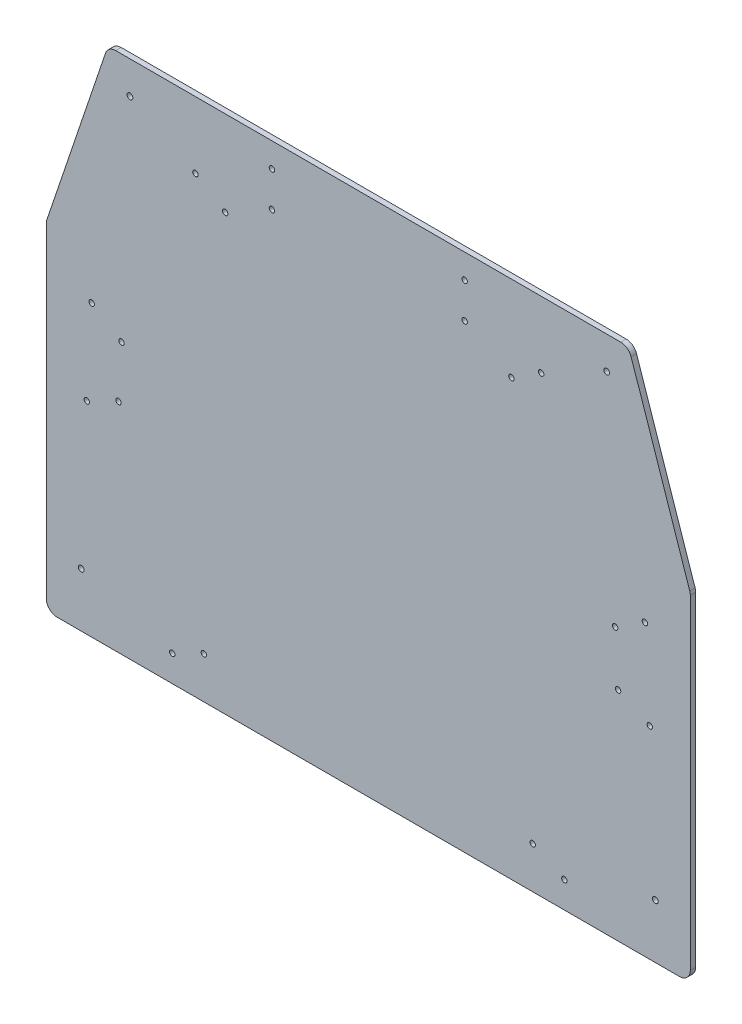
SolidWorks part; units mm, degrees
material "PC High Viscosity"
ref_plane "Front Plane" through (0, 0, 0) normal (0, 0, 1) x (1, 0, 0)
ref_plane "Top Plane" through (0, 0, 0) normal (0, 1, 0) x (1, 0, 0)
ref_plane "Right Plane" through (0, 0, 0) normal (1, 0, 0) x (0, 0, -1)
sketch "Sketch1" plane through (0, 0, 0) normal (0, 0, 1) x (1, 0, 0)
  line L0 (128.5466, 292.9716) -> (382.5466, 292.9716)
  line L5 (382.5466, 292.9716) -> (776.2466, -872.6346)
  line L6 (776.2466, -872.6346) -> (-265.1534, -872.6346)
  line L7 (-265.1534, -872.6346) -> (128.5466, 292.9716)
  line L8 (-168.2075, -740.392) -> (-160.0795, -716.3277) construction
  line L9 (-180.2397, -736.328) -> (-172.1116, -712.2636)
  line L10 (-156.1753, -744.4561) -> (-148.0473, -720.3917)
  line L11 (-94.2317, -804.0546) -> (-68.8317, -804.0546) construction
  line L12 (-94.2317, -791.3546) -> (-68.8317, -791.3546)
  line L13 (-94.2317, -816.7546) -> (-68.8317, -816.7546)
  line L14 (580.5201, -804.0546) -> (605.9201, -804.0546) construction
  line L15 (580.5201, -791.3546) -> (605.9201, -791.3546)
  line L16 (580.5201, -816.7546) -> (605.9201, -816.7546)
  line L17 (-56.7399, -410.3759) -> (-48.6118, -386.3115) construction
  line L18 (-68.7721, -406.3118) -> (-60.644, -382.2474)
  line L19 (-44.7077, -414.4399) -> (-36.5796, -390.3755)
  line L20 (45.2346, -108.4656) -> (53.3626, -84.4012) construction
  line L21 (33.2024, -104.4015) -> (41.3305, -80.3372)
  line L22 (57.2668, -112.5296) -> (65.3948, -88.4652)
  line L29 (139.9814, 172.0464) -> (148.1095, 196.1108) construction
  line L30 (127.9493, 176.1104) -> (136.0773, 200.1748)
  line L31 (152.0136, 167.9823) -> (160.1417, 192.0467)
  line L32 (192.1135, 241.2472) -> (217.5135, 241.2472) construction
  line L33 (192.1135, 253.9472) -> (217.5135, 253.9472)
  line L34 (192.1135, 228.5472) -> (217.5135, 228.5472)
  line L35 (293.6466, 241.2472) -> (319.0466, 241.2472) construction
  line L36 (293.6466, 253.9472) -> (319.0466, 253.9472)
  line L37 (293.6466, 228.5472) -> (319.0466, 228.5472)
  line L38 (371.0972, 172.0897) -> (362.9691, 196.154) construction
  line L39 (359.065, 168.0256) -> (350.9369, 192.09)
  line L40 (383.1294, 176.1537) -> (375.0013, 200.2181)
  line L41 (465.8587, -108.4656) -> (457.7306, -84.4012) construction
  line L42 (453.8265, -112.5296) -> (445.6984, -88.4652)
  line L43 (477.8909, -104.4015) -> (469.7628, -80.3372)
  line L44 (679.3008, -740.392) -> (671.1727, -716.3277) construction
  line L47 (567.8332, -410.3759) -> (559.7051, -386.3115) construction
  line L48 (555.801, -414.4399) -> (547.6729, -390.3755)
  line L49 (579.8654, -406.3118) -> (571.7373, -382.2474)
  line L50 (667.2686, -744.4561) -> (659.1405, -720.3917)
  line L53 (691.333, -736.328) -> (683.2049, -712.2636)
  circle A0 centre (396.7562, 191.3716) radius 5.3578
  circle A1 centre (114.6592, 192.3252) radius 5.3578
  circle A2 centre (-193.5708, -720.2346) radius 5.3578
  circle A4 centre (704.6641, -720.2346) radius 5.3578
  circle A5 centre (491.1275, -88.0284) radius 5.3578
  circle A6 centre (593.2201, -390.2884) radius 5.3578
  circle A7 centre (19.9658, -88.0284) radius 5.3578
  circle A8 centre (-82.1268, -390.2884) radius 5.3578
  circle A9 centre (306.3466, 271.7272) radius 5.3578
  circle A10 centre (204.7466, 271.7272) radius 5.3578
  circle A12 centre (-82.1268, -834.5346) radius 5.3578
  circle A13 centre (593.2201, -834.5346) radius 5.3578
  arc A14 (-180.2397, -736.328) -> (-156.1753, -744.4561) centre (-168.2075, -740.392) ccw
  arc A15 (-148.0473, -720.3917) -> (-172.1116, -712.2636) centre (-160.0795, -716.3277) ccw
  arc A16 (-94.2317, -791.3546) -> (-94.2317, -816.7546) centre (-94.2317, -804.0546) ccw
  arc A17 (-68.8317, -816.7546) -> (-68.8317, -791.3546) centre (-68.8317, -804.0546) ccw
  arc A18 (580.5201, -791.3546) -> (580.5201, -816.7546) centre (580.5201, -804.0546) ccw
  arc A19 (605.9201, -816.7546) -> (605.9201, -791.3546) centre (605.9201, -804.0546) ccw
  arc A20 (-68.7721, -406.3118) -> (-44.7077, -414.4399) centre (-56.7399, -410.3759) ccw
  arc A21 (-36.5796, -390.3755) -> (-60.644, -382.2474) centre (-48.6118, -386.3115) ccw
  arc A22 (33.2024, -104.4015) -> (57.2668, -112.5296) centre (45.2346, -108.4656) ccw
  arc A23 (65.3948, -88.4652) -> (41.3305, -80.3372) centre (53.3626, -84.4012) ccw
  arc A28 (127.9493, 176.1104) -> (152.0136, 167.9823) centre (139.9814, 172.0464) ccw
  arc A29 (160.1417, 192.0467) -> (136.0773, 200.1748) centre (148.1095, 196.1108) ccw
  arc A30 (192.1135, 253.9472) -> (192.1135, 228.5472) centre (192.1135, 241.2472) ccw
  arc A31 (217.5135, 228.5472) -> (217.5135, 253.9472) centre (217.5135, 241.2472) ccw
  arc A32 (293.6466, 253.9472) -> (293.6466, 228.5472) centre (293.6466, 241.2472) ccw
  arc A33 (319.0466, 228.5472) -> (319.0466, 253.9472) centre (319.0466, 241.2472) ccw
  arc A34 (359.065, 168.0256) -> (383.1294, 176.1537) centre (371.0972, 172.0897) ccw
  arc A35 (375.0013, 200.2181) -> (350.9369, 192.09) centre (362.9691, 196.154) ccw
  arc A36 (453.8265, -112.5296) -> (477.8909, -104.4015) centre (465.8587, -108.4656) ccw
  arc A37 (469.7628, -80.3372) -> (445.6984, -88.4652) centre (457.7306, -84.4012) ccw
  arc A40 (555.801, -414.4399) -> (579.8654, -406.3118) centre (567.8332, -410.3759) ccw
  arc A41 (571.7373, -382.2474) -> (547.6729, -390.3755) centre (559.7051, -386.3115) ccw
  arc A44 (667.2686, -744.4561) -> (691.333, -736.328) centre (679.3008, -740.392) ccw
  arc A45 (683.2049, -712.2636) -> (659.1405, -720.3917) centre (671.1727, -716.3277) ccw
  point P24 (-164.1435, -728.3598)
  point P39 (-81.5317, -804.0546)
  point P47 (593.2201, -804.0546)
  point P56 (-52.6759, -398.3437)
  point P62 (204.8135, 241.2472)
  point P65 (49.2986, -96.4334)
  point P93 (144.0455, 184.0786)
  point P106 (306.3466, 241.2472)
  point P115 (367.0332, 184.1219)
  point P125 (461.7947, -96.4334)
  point P136 (675.2368, -728.3598)
  point P140 (563.7691, -398.3437)
  dimension "D5" = 10.7156
  dimension "D6" = 19.05
  dimension "D7" = 17.78
  dimension "D8" = 17.78
  dimension "D9" = 17.78
  dimension "D10" = 17.78
  dimension "D11" = 17.78
  dimension "D12" = 17.78
  dimension "D13" = 38.1
  dimension "D31" = 183.6216
  dimension "D32" = 144.2748
  dimension "D36" = 108.893
  dimension "D37" = 17.78
  dimension "D41" = 76.2669
  dimension "D34" = 776.2012
  dimension "D35" = 25.4
  dimension "D1" = 254
  dimension "D2" = 1230.2998
  dimension "D3" = 1230.2998
  dimension "D4" = 1041.4
  dimension "D14" = 19.05
  dimension "D15" = 683.26
  dimension "D16" = 19.05
  dimension "D17" = 76.2
  dimension "D18" = 381
  dimension "D19" = 683.26
  dimension "D20" = 152.4
  dimension "D21" = 152.4
  dimension "D22" = 19.05
  dimension "D23" = 76.2
  dimension "D24" = 19.05
  dimension "D25" = 381
  dimension "D26" = 101.6
  dimension "D27" = 19.05
  dimension "D28" = 19.05
  dimension "D29" = 19.05
  dimension "D30" = 101.6
  dimension "D33" = 474.291
  dimension "D38" = 38.1
  dimension "D39" = 25.4
  dimension "D40" = 17.78
  dimension "D42" = 17.78
  dimension "D43" = 108.8497
  dimension "D47" = 17.78
  dimension "D52" = 17.78
  dimension "D53" = 17.78
  dimension "D56" = 21.2444
  dimension "D57" = 21.2444
extrude "Boss-Extrude1" add sketch "Sketch1" along normal blind 6.35 contours L7 L6 L5 L0 A29 L31 A28 L30 A23 L22 A22 L21 A21 L19 A20 L18 A19 L16 A18 L15 A17 L13 A16 L12 A15 L10 A14 L9 A13 A12 A10 A9 A8 A7 A6 A5
fillet "Fillet1" radius 6.35 4 edges at (-265.1534, -872.6346, 3.175) (776.2466, -872.6346, 3.175) (382.5466, 292.9716, 3.175) (128.5466, 292.9716, 3.175)
sketch "Sketch2" plane through (0, 0, 6.35) normal (0, 0, 1) x (1, 0, 0)
  line L0 (255.5466, -872.6346) -> (255.5466, 292.9716) construction
  line L1 (767.3994, -872.6346) -> (-256.3061, -872.6346) construction
  line L2 (133.1043, 292.9716) -> (377.989, 292.9716) construction
  line L3 (91.6472, -808.2573) -> (67.9728, -842.0678)
  line L4 (443.1205, -842.0678) -> (419.4461, -808.2573)
  arc A0 (91.6472, -808.2573) -> (419.4461, -808.2573) centre (255.5466, -574.1846) cw
  arc A1 (67.9728, -842.0678) -> (443.1205, -842.0678) centre (255.5466, -574.1846) cw
  point P0 (255.5466, -288.4346)
  dimension "D3" = 298.45
  dimension "D1" = 41.275
  dimension "D2" = 584.2
  dimension "D4" = 70
sketch "Sketch4" plane through (0, 0, 6.35) normal (0, 0, 1) x (1, 0, 0)
  line L0 (414.1087, -288.4346) -> (255.5466, -288.4346)
  line L13 (414.1087, -288.4346) -> (572.6707, -563.0721)
  line L14 (572.6707, -563.0721) -> (414.1087, -837.7096)
  line L15 (767.3994, -872.6346) -> (-256.3061, -872.6346) construction
  line L16 (255.5466, -288.4346) -> (255.5466, -872.6346) construction
  line L17 (437.9388, -247.1596) -> (255.5466, -247.1596)
  line L18 (437.9388, -247.1596) -> (620.331, -563.0721)
  line L19 (620.331, -563.0721) -> (449.8539, -858.3471)
  line L20 (449.8539, -858.3471) -> (414.1087, -837.7096)
  line L21 (61.2394, -858.3471) -> (96.9846, -837.7096)
  line L22 (-109.2377, -563.0721) -> (61.2394, -858.3471)
  line L23 (73.1545, -247.1596) -> (-109.2377, -563.0721)
  line L24 (73.1545, -247.1596) -> (255.5466, -247.1596)
  line L25 (-61.5774, -563.0721) -> (96.9846, -837.7096)
  line L26 (96.9846, -288.4346) -> (-61.5774, -563.0721)
  line L27 (96.9846, -288.4346) -> (255.5466, -288.4346)
  line L28 (414.1087, -837.7096) -> (96.9846, -837.7096) construction
  dimension "D1" = 309.5625
  dimension "D2" = 317.1241
  dimension "D3" = 120
  dimension "D4" = 120
  dimension "D5" = 41.275
extrude "Cut-Extrude1" cut sketch "Sketch2" against normal through all
extrude "Cut-Extrude2" [suppressed] cut sketch "Sketch4" against normal through all
sketch "Sketch5" plane through (0, 0, 6.35) normal (0, 0, 1) x (1, 0, 0)
  line L0 (57.2668, -112.5296) -> (65.3948, -88.4652) construction
  line L1 (33.2024, -104.4015) -> (41.3305, -80.3372) construction
  line L2 (-44.7077, -414.4399) -> (-36.5796, -390.3755) construction
  line L3 (-68.7721, -406.3118) -> (-60.644, -382.2474) construction
  line L4 (-180.2397, -736.328) -> (-172.1116, -712.2636) construction
  line L5 (-156.1753, -744.4561) -> (-148.0473, -720.3917) construction
  line L6 (-94.2317, -816.7546) -> (-68.8317, -816.7546) construction
  line L7 (-94.2317, -791.3546) -> (-68.8317, -791.3546) construction
  line L8 (57.2668, -112.5296) -> (65.3948, -88.4652)
  line L9 (33.2024, -104.4015) -> (41.3305, -80.3372)
  line L10 (-44.7077, -414.4399) -> (-36.5796, -390.3755)
  line L11 (-68.7721, -406.3118) -> (-60.644, -382.2474)
  line L12 (-180.2397, -736.328) -> (-172.1116, -712.2636)
  line L13 (-156.1753, -744.4561) -> (-148.0473, -720.3917)
  line L14 (-94.2317, -816.7546) -> (-68.8317, -816.7546)
  line L15 (-94.2317, -791.3546) -> (-68.8317, -791.3546)
  line L16 (192.1135, 228.5472) -> (217.5135, 228.5472) construction
  line L17 (192.1135, 253.9472) -> (217.5135, 253.9472) construction
  line L18 (152.0136, 167.9823) -> (160.1417, 192.0467) construction
  line L19 (127.9493, 176.1104) -> (136.0773, 200.1748) construction
  line L20 (192.1135, 228.5472) -> (217.5135, 228.5472)
  line L21 (192.1135, 253.9472) -> (217.5135, 253.9472)
  line L22 (152.0136, 167.9823) -> (160.1417, 192.0467)
  line L23 (127.9493, 176.1104) -> (136.0773, 200.1748)
  line L24 (255.5466, 292.9716) -> (255.5466, -872.6346) construction
  line L37 (359.065, 168.0256) -> (350.9369, 192.09) construction
  line L38 (383.1294, 176.1537) -> (375.0013, 200.2181) construction
  line L39 (293.6466, 228.5472) -> (319.0466, 228.5472) construction
  line L40 (293.6466, 253.9472) -> (319.0466, 253.9472) construction
  line L41 (359.065, 168.0256) -> (350.9369, 192.09)
  line L42 (383.1294, 176.1537) -> (375.0013, 200.2181)
  line L43 (293.6466, 228.5472) -> (319.0466, 228.5472)
  line L44 (293.6466, 253.9472) -> (319.0466, 253.9472)
  line L45 (453.8265, -112.5296) -> (445.6984, -88.4652) construction
  line L46 (477.8909, -104.4015) -> (469.7628, -80.3372) construction
  line L47 (453.8265, -112.5296) -> (445.6984, -88.4652)
  line L48 (477.8909, -104.4015) -> (469.7628, -80.3372)
  line L49 (555.801, -414.4399) -> (547.6729, -390.3755) construction
  line L50 (579.8654, -406.3118) -> (571.7373, -382.2474) construction
  line L51 (555.801, -414.4399) -> (547.6729, -390.3755)
  line L52 (579.8654, -406.3118) -> (571.7373, -382.2474)
  line L53 (667.2686, -744.4561) -> (659.1405, -720.3917) construction
  line L54 (691.333, -736.328) -> (683.2049, -712.2636) construction
  line L55 (667.2686, -744.4561) -> (659.1405, -720.3917)
  line L56 (691.333, -736.328) -> (683.2049, -712.2636)
  line L57 (580.5201, -791.3546) -> (605.9201, -791.3546) construction
  line L58 (580.5201, -816.7546) -> (605.9201, -816.7546) construction
  line L59 (580.5201, -791.3546) -> (605.9201, -791.3546)
  line L60 (580.5201, -816.7546) -> (605.9201, -816.7546)
  arc A0 (33.2024, -104.4015) -> (57.2668, -112.5296) centre (45.2346, -108.4656) ccw construction
  arc A1 (65.3948, -88.4652) -> (41.3305, -80.3372) centre (53.3626, -84.4012) ccw construction
  circle A2 centre (19.9658, -88.0284) radius 5.3578 construction
  arc A3 (-68.7721, -406.3118) -> (-44.7077, -414.4399) centre (-56.7399, -410.3759) ccw construction
  circle A4 centre (-82.1268, -390.2884) radius 5.3578 construction
  arc A5 (-36.5796, -390.3755) -> (-60.644, -382.2474) centre (-48.6118, -386.3115) ccw construction
  circle A6 centre (-193.5708, -720.2346) radius 5.3578 construction
  arc A7 (-148.0473, -720.3917) -> (-172.1116, -712.2636) centre (-160.0795, -716.3277) ccw construction
  arc A8 (-180.2397, -736.328) -> (-156.1753, -744.4561) centre (-168.2075, -740.392) ccw construction
  arc A9 (-94.2317, -791.3546) -> (-94.2317, -816.7546) centre (-94.2317, -804.0546) ccw construction
  arc A10 (-68.8317, -816.7546) -> (-68.8317, -791.3546) centre (-68.8317, -804.0546) ccw construction
  circle A11 centre (-82.1268, -834.5346) radius 5.3578 construction
  arc A12 (33.2024, -104.4015) -> (57.2668, -112.5296) centre (45.2346, -108.4656) ccw
  arc A13 (65.3948, -88.4652) -> (41.3305, -80.3372) centre (53.3626, -84.4012) ccw
  circle A14 centre (19.9658, -88.0284) radius 5.3578
  arc A15 (-68.7721, -406.3118) -> (-44.7077, -414.4399) centre (-56.7399, -410.3759) ccw
  circle A16 centre (-82.1268, -390.2884) radius 5.3578
  arc A17 (-36.5796, -390.3755) -> (-60.644, -382.2474) centre (-48.6118, -386.3115) ccw
  circle A18 centre (-193.5708, -720.2346) radius 5.3578
  arc A19 (-148.0473, -720.3917) -> (-172.1116, -712.2636) centre (-160.0795, -716.3277) ccw
  arc A20 (-180.2397, -736.328) -> (-156.1753, -744.4561) centre (-168.2075, -740.392) ccw
  arc A21 (-94.2317, -791.3546) -> (-94.2317, -816.7546) centre (-94.2317, -804.0546) ccw
  arc A22 (-68.8317, -816.7546) -> (-68.8317, -791.3546) centre (-68.8317, -804.0546) ccw
  circle A23 centre (-82.1268, -834.5346) radius 5.3578
  arc A24 (217.5135, 228.5472) -> (217.5135, 253.9472) centre (217.5135, 241.2472) ccw construction
  arc A25 (192.1135, 253.9472) -> (192.1135, 228.5472) centre (192.1135, 241.2472) ccw construction
  circle A26 centre (204.7466, 271.7272) radius 5.3578 construction
  arc A27 (127.9493, 176.1104) -> (152.0136, 167.9823) centre (139.9814, 172.0464) ccw construction
  arc A28 (160.1417, 192.0467) -> (136.0773, 200.1748) centre (148.1095, 196.1108) ccw construction
  circle A29 centre (114.6592, 192.3252) radius 5.3578 construction
  arc A30 (217.5135, 228.5472) -> (217.5135, 253.9472) centre (217.5135, 241.2472) ccw
  arc A31 (192.1135, 253.9472) -> (192.1135, 228.5472) centre (192.1135, 241.2472) ccw
  circle A32 centre (204.7466, 271.7272) radius 5.3578
  arc A33 (127.9493, 176.1104) -> (152.0136, 167.9823) centre (139.9814, 172.0464) ccw
  arc A34 (160.1417, 192.0467) -> (136.0773, 200.1748) centre (148.1095, 196.1108) ccw
  circle A35 centre (114.6592, 192.3252) radius 5.3578
  circle A54 centre (306.3466, 271.7272) radius 5.3578 construction
  circle A55 centre (306.3466, 271.7272) radius 5.3578
  circle A56 centre (396.7562, 191.3716) radius 5.3578 construction
  arc A57 (359.065, 168.0256) -> (383.1294, 176.1537) centre (371.0972, 172.0897) ccw construction
  arc A58 (375.0013, 200.2181) -> (350.9369, 192.09) centre (362.9691, 196.154) ccw construction
  arc A59 (293.6466, 253.9472) -> (293.6466, 228.5472) centre (293.6466, 241.2472) ccw construction
  arc A60 (319.0466, 228.5472) -> (319.0466, 253.9472) centre (319.0466, 241.2472) ccw construction
  circle A61 centre (396.7562, 191.3716) radius 5.3578
  arc A62 (359.065, 168.0256) -> (383.1294, 176.1537) centre (371.0972, 172.0897) ccw
  arc A63 (375.0013, 200.2181) -> (350.9369, 192.09) centre (362.9691, 196.154) ccw
  arc A64 (293.6466, 253.9472) -> (293.6466, 228.5472) centre (293.6466, 241.2472) ccw
  arc A65 (319.0466, 228.5472) -> (319.0466, 253.9472) centre (319.0466, 241.2472) ccw
  arc A66 (453.8265, -112.5296) -> (477.8909, -104.4015) centre (465.8587, -108.4656) ccw construction
  arc A67 (469.7628, -80.3372) -> (445.6984, -88.4652) centre (457.7306, -84.4012) ccw construction
  circle A68 centre (491.1275, -88.0284) radius 5.3578 construction
  arc A69 (453.8265, -112.5296) -> (477.8909, -104.4015) centre (465.8587, -108.4656) ccw
  arc A70 (469.7628, -80.3372) -> (445.6984, -88.4652) centre (457.7306, -84.4012) ccw
  circle A71 centre (491.1275, -88.0284) radius 5.3578
  arc A72 (555.801, -414.4399) -> (579.8654, -406.3118) centre (567.8332, -410.3759) ccw construction
  circle A73 centre (593.2201, -390.2884) radius 5.3578 construction
  arc A74 (571.7373, -382.2474) -> (547.6729, -390.3755) centre (559.7051, -386.3115) ccw construction
  arc A75 (555.801, -414.4399) -> (579.8654, -406.3118) centre (567.8332, -410.3759) ccw
  circle A76 centre (593.2201, -390.2884) radius 5.3578
  arc A77 (571.7373, -382.2474) -> (547.6729, -390.3755) centre (559.7051, -386.3115) ccw
  arc A78 (667.2686, -744.4561) -> (691.333, -736.328) centre (679.3008, -740.392) ccw construction
  arc A79 (683.2049, -712.2636) -> (659.1405, -720.3917) centre (671.1727, -716.3277) ccw construction
  circle A80 centre (704.6641, -720.2346) radius 5.3578 construction
  arc A81 (667.2686, -744.4561) -> (691.333, -736.328) centre (679.3008, -740.392) ccw
  arc A82 (683.2049, -712.2636) -> (659.1405, -720.3917) centre (671.1727, -716.3277) ccw
  circle A83 centre (704.6641, -720.2346) radius 5.3578
  arc A84 (605.9201, -816.7546) -> (605.9201, -791.3546) centre (605.9201, -804.0546) ccw construction
  circle A85 centre (593.2201, -834.5346) radius 5.3578 construction
  arc A86 (580.5201, -791.3546) -> (580.5201, -816.7546) centre (580.5201, -804.0546) ccw construction
  arc A87 (605.9201, -816.7546) -> (605.9201, -791.3546) centre (605.9201, -804.0546) ccw
  circle A88 centre (593.2201, -834.5346) radius 5.3578
  arc A89 (580.5201, -791.3546) -> (580.5201, -816.7546) centre (580.5201, -804.0546) ccw
extrude "Boss-Extrude2" [suppressed] add sketch "Sketch5" against normal up to surface (6.35 mm away)
ref_plane "Plane1" through (0, 0, -63.5) normal (0, 0, -1) x (-1, 0, 0)
sketch "Sketch7" plane through (0, 0, -63.5) normal (0, 0, -1) x (-1, 0, 0)
  line L0 (121.9377, -872.6346) -> (-633.031, -872.6346)
  line L1 (-767.3994, -872.6346) -> (256.3061, -872.6346) construction
  line L2 (121.9377, -872.6346) -> (121.9377, -448.6238)
  line L3 (262.3222, -864.2526) -> (-127.0882, 288.6536) construction
  line L4 (121.9377, -448.6238) -> (36.7319, -196.3596)
  line L5 (36.7319, -196.3596) -> (-547.8252, -196.3596)
  line L6 (-255.5466, -872.6346) -> (-255.5466, 292.9716) construction
  line L7 (-255.5466, -872.6346) -> (-255.5466, -196.3596) construction
  line L8 (-633.031, -448.6238) -> (-547.8252, -196.3596)
  line L9 (-633.031, -872.6346) -> (-633.031, -448.6238)
  line L10 (-73.1545, -247.1596) -> (-255.5466, -247.1596) construction
  dimension "D1" = 12.7
  dimension "D2" = 50.8
extrude "Boss-Extrude3" add sketch "Sketch7" along normal blind 6.35 separate body
hole_wizard "1/4 (0.25) Diameter Hole3" [suppressed] positions "Sketch8" profile "Sketch9" hole size "1/4" standard "ANSI Inch"
sketch "Sketch8" plane through (0, 0, -69.85) normal (0, 0, -1) x (-1, 0, 0)
  line L0 (-431.9813, -848.0284) -> (-596.5008, -563.0721) construction
  line L1 (-449.8539, -858.3471) -> (-414.1087, -837.7096) construction
  line L2 (-596.5008, -563.0721) -> (-426.0237, -267.7971) construction
  line L3 (-426.0237, -267.7971) -> (-255.5466, -267.7971) construction
  line L4 (-255.5466, -872.6346) -> (-255.5466, 292.9716) construction
  line L6 (-620.331, -563.0721) -> (-572.6707, -563.0721) construction
  line L7 (-255.5466, -247.1596) -> (-255.5466, -288.4346) construction
  line L8 (-437.9388, -247.1596) -> (-620.331, -563.0721) construction
  line L9 (-414.1087, -837.7096) -> (-572.6707, -563.0721) construction
  line L10 (-572.6707, -563.0721) -> (-414.1087, -288.4346) construction
  line L11 (-414.1087, -288.4346) -> (-255.5466, -288.4346) construction
  line L12 (-449.8539, -858.3471) -> (-620.331, -563.0721) construction
  line L13 (-620.331, -563.0721) -> (-437.9388, -247.1596) construction
  line L14 (-437.9388, -247.1596) -> (-255.5466, -247.1596) construction
  line L15 (-255.5466, -288.4346) -> (-255.5466, -872.6346) construction
  point P29 (-484.7789, -797.8553)
  point P52 (-573.4909, -644.2015)
  point P56 (-537.7457, -623.564)
  point P57 (-449.0337, -777.2178)
  point P59 (-573.4909, -481.9428)
  point P61 (-484.7789, -328.289)
  point P65 (-537.7457, -502.5803)
  point P66 (-449.0337, -348.9265)
  point P69 (-344.2587, -288.4346)
  point P74 (-344.2587, -247.1596)
  point P76 (-62.0596, -777.2178)
  point P77 (-26.3144, -797.8553)
  point P78 (26.6524, -623.564)
  point P79 (62.3976, -644.2015)
  point P80 (26.6524, -502.5803)
  point P81 (62.3976, -481.9428)
  point P82 (-62.0596, -348.9265)
  point P83 (-26.3144, -328.289)
  point P84 (-166.8346, -247.1596)
  point P85 (-166.8346, -288.4346)
  dimension "D6" = 317.1241
  dimension "D7" = 317.1241
  dimension "D8" = 317.1241
  dimension "D3" = 69.85
  dimension "D4" = 69.85
  dimension "D5" = 69.85
  dimension "D9" = 69.85
  dimension "D10" = 69.85
  dimension "D1" = 20.6375
  dimension "D2" = 20.6375
sketch "Sketch9" plane through (166.8346, -288.4346, -69.85) normal (1, 0, 0) x (0, 1, 0)
  line L0 (0, 0) -> (0, 76.2)
  line L1 (0, 76.2) -> (3.175, 76.2)
  line L2 (3.175, 76.2) -> (3.175, 0)
  line L5 (3.175, 0) -> (0, 0)
  line L11 (0, -6.35) -> (0, 107.95) construction
  dimension "Thru Hole Dia." = 6.35
  dimension "Thru Hole Depth" = 76.2
hole_wizard "1/4 (0.25) Diameter Hole4" positions "Sketch12" profile "Sketch13" hole size "1/4" standard "ANSI Inch" end condition through all
sketch "Sketch12" plane through (0, 0, -69.85) normal (0, 0, -1) x (-1, 0, 0)
  line L1 (-602.0552, -565.6572) -> (-570.6386, -550.4009) construction
  line L2 (-602.0552, -565.6572) -> (-463.1129, -851.7763) construction
  line L3 (-570.6386, -550.4009) -> (-431.6962, -836.5201) construction
  line L4 (-463.1129, -851.7763) -> (-431.6962, -836.5201) construction
  line L5 (-582.0628, -555.9487) -> (-443.1205, -842.0678) construction
  line L6 (-600.8498, -544.0743) -> (-571.3274, -562.734) construction
  line L7 (-600.8498, -544.0743) -> (-431.7672, -276.5603) construction
  line L8 (-571.3274, -562.734) -> (-402.2448, -295.22) construction
  line L9 (-431.7672, -276.5603) -> (-402.2448, -295.22) construction
  line L10 (-582.0628, -555.9487) -> (-412.9802, -288.4346) construction
  line L11 (-412.9802, -266.2096) -> (-412.9802, -301.1346) construction
  line L12 (-412.9802, -266.2096) -> (-98.1131, -266.2096) construction
  line L13 (-412.9802, -301.1346) -> (-98.1131, -301.1346) construction
  line L14 (-98.1131, -266.2096) -> (-98.1131, -301.1346) construction
  line L15 (-412.9802, -288.4346) -> (-96.5111, -288.4346) construction
  line L16 (-255.5466, -301.1346) -> (-255.5466, -872.6346) construction
  line L29 (-585.4942, -607.0289) -> (-548.3655, -588.9988) construction
  line L30 (-485.3859, -813.1785) -> (-448.2572, -795.1484) construction
  line L31 (-458.1997, -312.4379) -> (-423.3096, -334.4903) construction
  line L32 (-458.1997, -312.4379) -> (-579.785, -504.804) construction
  line L33 (-579.785, -504.804) -> (-544.8948, -526.8564) construction
  line L34 (-368.5302, -263.0346) -> (-368.5302, -304.3096) construction
  arc A0 (-91.6472, -808.2573) -> (-419.4461, -808.2573) centre (-255.5466, -574.1846) ccw construction
  arc A1 (-67.9728, -842.0678) -> (-443.1205, -842.0678) centre (-255.5466, -574.1846) ccw construction
  point P371 (-485.3859, -813.1785)
  point P519 (-585.4942, -607.0289)
  point P528 (-548.3655, -588.9988)
  point P535 (-448.2572, -795.1484)
  point P538 (-544.8948, -526.8564)
  point P540 (-579.785, -504.804)
  point P542 (-423.3096, -334.4903)
  point P544 (-458.1997, -312.4379)
  point P560 (-368.5302, -263.0346)
  point P570 (-368.5302, -304.3096)
  point P573 (-142.5631, -304.3096)
  point P574 (-142.5631, -263.0346)
  point P575 (-52.8935, -312.4379)
  point P576 (-87.7837, -334.4903)
  point P577 (68.6917, -504.804)
  point P578 (33.8016, -526.8564)
  point P579 (-62.8361, -795.1484)
  point P580 (37.2722, -588.9988)
  point P581 (74.401, -607.0289)
  point P582 (-25.7073, -813.1785)
  dimension "D1" = 34.925
  dimension "D11" = 12.7
  dimension "D12" = 12.7
  dimension "D13" = 12.7
  dimension "D2" = 44.45
  dimension "D3" = 3.175
  dimension "D4" = 44.45
  dimension "D5" = 3.175
  dimension "D6" = 3.175
  dimension "D7" = 3.175
  dimension "D8" = 44.45
  dimension "D9" = 44.45
  dimension "D10" = 3.175
  dimension "D14" = 44.45
sketch "Sketch13" plane through (25.7073, -813.1785, -69.85) normal (1, 0, 0) x (0, 1, 0)
  line L0 (0, 0) -> (0, 76.2)
  line L1 (0, 76.2) -> (3.175, 76.2)
  line L2 (3.175, 76.2) -> (3.175, 0)
  line L5 (3.175, 0) -> (0, 0)
  line L11 (0, -6.35) -> (0, 107.95) construction
  dimension "Thru Hole Dia." = 6.35
  dimension "Thru Hole Depth" = 76.2
sketch "Sketch14" plane through (0, 0, -69.85) normal (0, 0, -1) x (-1, 0, 0)
  line L0 (-567.551, -556.7591) -> (-431.6962, -836.5201)
  line L1 (-570.6386, -550.4009) -> (-431.6962, -836.5201) construction
  line L2 (-571.3274, -562.734) -> (-402.2448, -295.22) construction
  line L3 (-567.551, -556.7591) -> (-405.9832, -301.1346)
  line L4 (-412.9802, -301.1346) -> (-98.1131, -301.1346) construction
  line L5 (-405.9832, -301.1346) -> (-105.1101, -301.1346)
  line L6 (-255.5466, -872.6346) -> (-255.5466, 292.9716) construction
  point P10 (-255.5466, -301.1346)
  dimension "D1" = 311.0027
  dimension "D2" = 302.4038
  dimension "D3" = 300.8731
delete or keep bodies "Body-Delete/Keep 1" type delete bodies bodies 105
sketch "Sketch15" plane through (0, 0, -63.5) normal (0, 0, 1) x (1, 0, 0)
  line L0 (633.031, -448.6238) -> (633.031, -872.6346) construction
  line L1 (-121.9377, -872.6346) -> (633.031, -872.6346)
  line L2 (-121.9377, -872.6346) -> (-121.9377, -844.0596)
  line L3 (-121.9377, -844.0596) -> (633.031, -844.0596)
  line L4 (633.031, -872.6346) -> (633.031, -844.0596)
  dimension "D1" = 28.575
extrude "Cut-Extrude3" cut sketch "Sketch15" against normal through all
sketch "Sketch16" plane through (0, 0, -63.5) normal (0, 0, 1) x (1, 0, 0)
  line L0 (633.031, -844.0596) -> (-121.9377, -844.0596) construction
  line L3 (255.5466, -196.3596) -> (255.5466, -844.0596) construction
  line L4 (-36.7319, -196.3596) -> (547.8252, -196.3596) construction
  line L5 (633.031, -844.0596) -> (-121.9377, -844.0596) construction
  point P0 (-81.0034, -780.5596)
  point P1 (-23.8534, -272.5596)
  point P2 (534.9466, -272.5596)
  point P3 (592.0966, -780.5596)
  dimension "D1" = 63.5
  dimension "D2" = 673.1
  dimension "D3" = 558.8
  dimension "D4" = 336.55
  dimension "D5" = 279.4
  dimension "D6" = 508
hole_wizard "17/64 (0.26563) Diameter Hole1" positions "Sketch17" profile "Sketch18" hole size "17/64" standard "ANSI Inch" end condition through all
sketch "Sketch17" plane through (0, 0, -63.5) normal (0, 0, 1) x (1, 0, 0)
  point P0 (-23.8534, -272.5596)
  point P3 (534.9466, -272.5596)
  point P6 (592.0966, -780.5596)
  point P9 (-81.0034, -780.5596)
sketch "Sketch18" plane through (-23.8534, -272.5596, -63.5) normal (1, 0, 0) x (0, -1, 0)
  line L0 (0, 0) -> (0, 6.35)
  line L1 (0, 6.35) -> (3.3735, 6.35)
  line L2 (3.3735, 6.35) -> (3.3735, 0)
  line L5 (3.3735, 0) -> (0, 0)
  line L11 (0, -6.35) -> (0, 107.95) construction
  dimension "Thru Hole Dia." = 6.747
  dimension "Thru Hole Depth" = 6.35
sketch "Sketch19" plane through (0, 0, -63.5) normal (0, 0, 1) x (1, 0, 0)
  line L0 (547.8252, -196.3596) -> (633.031, -448.6238) construction
  line L1 (-121.9377, -448.6238) -> (-36.7319, -196.3596) construction
  line L2 (-36.7319, -196.3596) -> (547.8252, -196.3596) construction
  line L3 (547.8252, -196.3596) -> (560.694, -234.4596)
  line L4 (-49.6007, -234.4596) -> (-36.7319, -196.3596)
  line L5 (-36.7319, -196.3596) -> (547.8252, -196.3596)
  line L6 (-49.6007, -234.4596) -> (560.694, -234.4596)
  dimension "D1" = 38.1
extrude "Cut-Extrude4" cut sketch "Sketch19" against normal through all
fillet "Fillet2" radius 12.7 6 edges at (633.031, -448.6238, -66.675) (-121.9377, -448.6238, -66.675) (-121.9377, -844.0596, -66.675) (633.031, -844.0596, -66.675) (560.694, -234.4596, -66.675) (-49.6007, -234.4596, -66.675)
equation "\"D2@Sketch8\"=1.375/2+.125"
equation "\"D1@Sketch8\"=\"D2@Sketch8\""
equation "\"D12@Sketch12\"=\"D11@Sketch12\""
